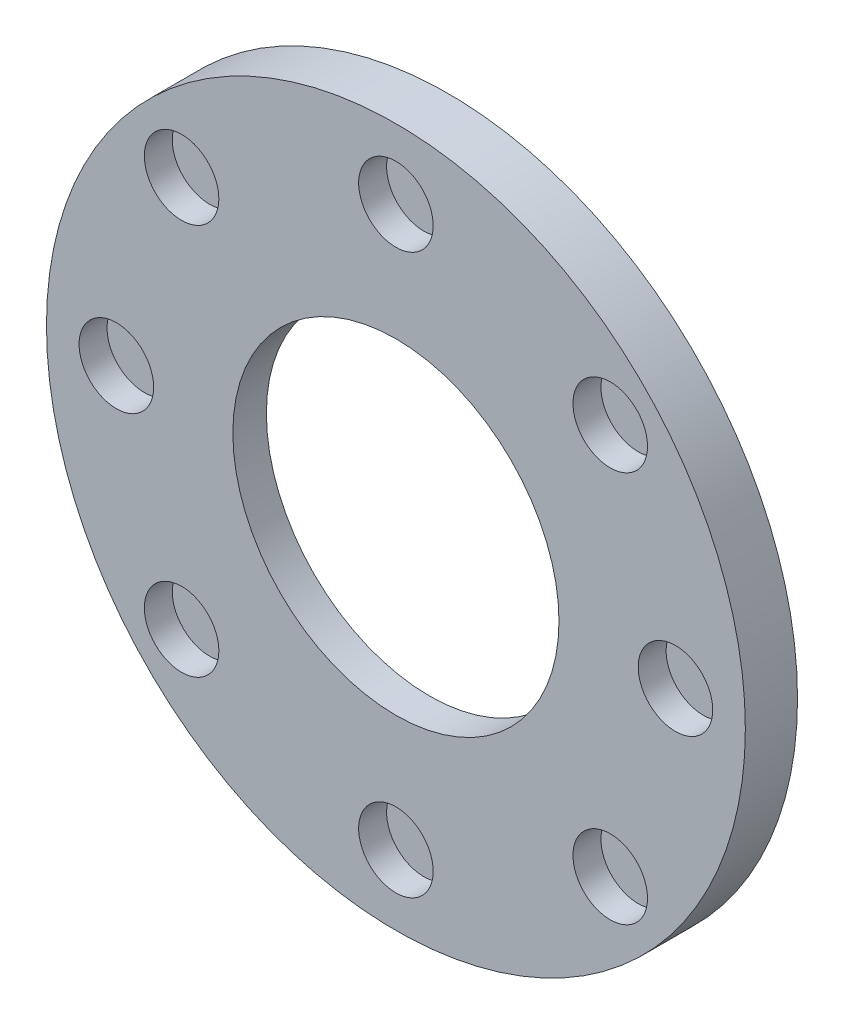
SolidWorks part; units mm, degrees
ref_plane "Спереди" through (0, 0, 0) normal (0, 0, 1) x (1, 0, 0)
ref_plane "Сверху" through (0, 0, 0) normal (0, 1, 0) x (1, 0, 0)
ref_plane "Справа" through (0, 0, 0) normal (1, 0, 0) x (0, 0, -1)
sketch "Эскиз1" plane through (0, 0, 0) normal (0, 0, 1) x (1, 0, 0)
  circle A0 centre (0, 0) radius 37.5
  circle A1 centre (0, 0) radius 25
  point P5 (0, 0)
  point P6 (0, 0)
  point P7 (0, 0)
  point P8 (0, 0)
  point P9 (0, 0)
  point P10 (0, 0)
  point P11 (0, 0)
  point P12 (0, 0)
  dimension "D1" = 75
extrude "Бобышка-Вытянуть1" add sketch "Эскиз1" along normal blind 2
sketch "Эскиз2" plane through (0, 0, 2) normal (0, 0, 1) x (1, 0, 0)
  circle A0 centre (0, 0) radius 37.5
  circle A1 centre (0, 0) radius 17.5
  dimension "D1" = 75
  dimension "D2" = 35
extrude "Бобышка-Вытянуть2" add sketch "Эскиз2" along normal blind 0.6
sketch "Эскиз3" plane through (0, 0, 2.6) normal (0, 0, 1) x (1, 0, 0)
  circle A0 centre (0, 0) radius 17.5
  circle A1 centre (0, 0) radius 37.5
  circle A2 centre (0, 30) radius 4
  circle A3 centre (0, -30) radius 4
  circle A4 centre (30, 0) radius 4
  circle A5 centre (-30, 0) radius 4
  circle A6 centre (23, 21) radius 4
  circle A7 centre (-23, 21) radius 4
  circle A8 centre (-23, -21) radius 4
  circle A9 centre (23, -21) radius 4
  dimension "D1" = 35
extrude "Бобышка-Вытянуть3" add sketch "Эскиз3" along normal blind 3
